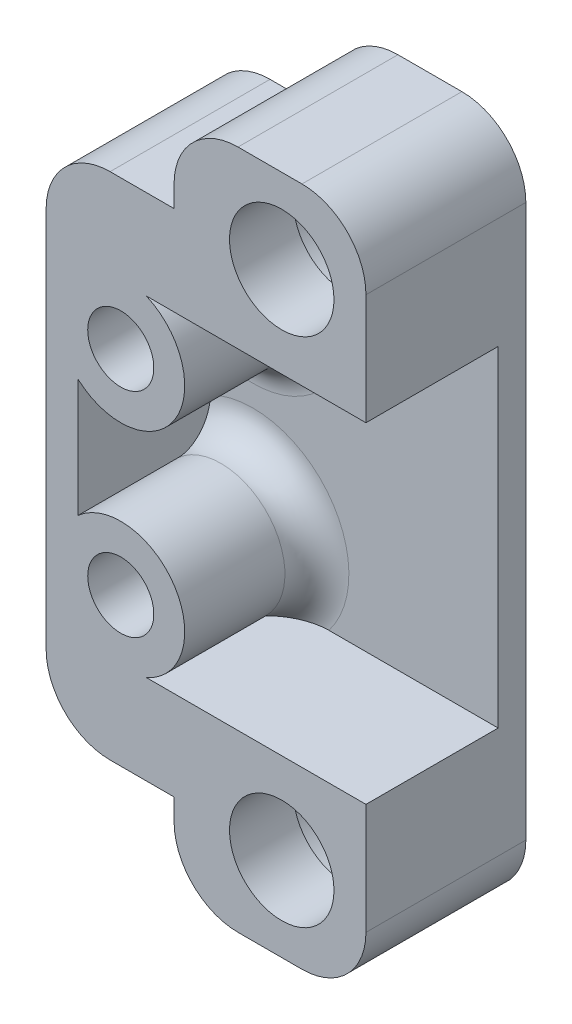
SolidWorks part; units mm, degrees
ref_plane "Front Plane" through (0, 0, 0) normal (0, 0, 1) x (1, 0, 0)
ref_plane "Top Plane" through (0, 0, 0) normal (0, 1, 0) x (1, 0, 0)
ref_plane "Right Plane" through (0, 0, 0) normal (1, 0, 0) x (0, 0, -1)
sketch "Sketch1" plane through (0, 0, 0) normal (0, 0, 1) x (1, 0, 0)
  line L0 (-10.2404, 15.95) -> (-10.2404, -15.95)
  line L1 (-6.2904, -12) -> (6.2904, -12)
  line L2 (-6.2904, -12) -> (-6.2904, 12)
  line L3 (-6.2904, 12) -> (6.2904, 12)
  line L4 (6.2904, -12) -> (6.2904, 12)
  line L5 (-6.2904, -12) -> (6.2904, 12) construction
  line L6 (-6.2904, 12) -> (6.2904, -12) construction
  line L7 (-8.7404, 14.45) -> (8.7404, 14.45)
  line L8 (-8.7404, 14.45) -> (-8.7404, -14.45)
  line L9 (-8.7404, -14.45) -> (8.7404, -14.45)
  line L10 (8.7404, 14.45) -> (8.7404, -14.45)
  line L11 (-8.7404, 14.45) -> (8.7404, -14.45) construction
  line L12 (-8.7404, -14.45) -> (8.7404, 14.45) construction
  line L13 (-10.2404, -15.95) -> (10.2404, -15.95)
  line L14 (10.2404, 15.95) -> (10.2404, -15.95)
  line L15 (-10.2404, 15.95) -> (10.2404, 15.95)
  circle A0 centre (6.2904, 12) radius 2.45
  circle A1 centre (6.2904, -12) radius 2.45
  point P0 (0, 0)
  point P8 (0, 0)
  dimension "D2" = 4.9
  dimension "D3" = 4.9
  dimension "D1" = 24
  dimension "D5" = 31.9
  dimension "D4" = 1.5
extrude "Boss-Extrude1" add sketch "Sketch1" along normal blind 7.5 contours L15 L0 L13 L14 L7 L10 L9 L8 | A0 L10 L7 | A1 L1 L2 L3 A0 L7 L8 L9 | A1 L10 A0 L4 | A1 L4 A0 L3 L2 L1 | A1 L9 L10
sketch "Sketch2" plane through (0, 0, 7.5) normal (0, 0, 1) x (1, 0, 0)
  line L0 (10.2404, 15.95) -> (8.7404, 15.95)
  line L1 (-10.2404, 15.95) -> (10.2404, 15.95) construction
  line L2 (8.7404, 15.95) -> (8.7404, -15.95)
  line L3 (-10.2404, -15.95) -> (10.2404, -15.95) construction
  line L4 (8.7404, 0) -> (-10.2404, 0)
  line L5 (-10.2404, 15.95) -> (-10.2404, -15.95) construction
  line L7 (-10.2404, -9.35) -> (8.7404, -9.35)
  line L8 (-10.2404, -9.35) -> (-10.2404, 9.35)
  line L9 (-10.2404, 9.35) -> (8.7404, 9.35)
  line L10 (8.7404, -9.35) -> (8.7404, 9.35)
  line L11 (-10.2404, -9.35) -> (8.7404, 9.35) construction
  line L12 (-10.2404, 9.35) -> (8.7404, -9.35) construction
  point P12 (-0.75, 0)
  line M11 (-10.2404, 15.95) -> (-10.2404, -15.95)
  dimension "D1" = 1.5
  dimension "D2" = 18.7
extrude "Cut-Extrude1" cut sketch "Sketch2" against normal blind 6.2 contours L9 L4 L2 M11 | L7 L2 L4 M11
sketch "Sketch3" plane through (0, 0, 1.3) normal (0, 0, 1) x (1, 0, 0)
  line L0 (10.2404, 0) -> (-1.2596, 0)
  line L1 (10.2404, 15.95) -> (10.2404, -15.95) construction
  line L2 (-1.2596, -5) -> (-1.2596, 5)
  circle A0 centre (-1.2596, 5) radius 1.55
  circle A1 centre (-1.2596, -5) radius 1.55
  circle A2 centre (-1.2596, 5) radius 3
  circle A3 centre (-1.2596, -5) radius 3
  point P7 (-1.2596, 0)
  dimension "D3" = 3.1
  dimension "D4" = 3.1
  dimension "D5" = 6
  dimension "D6" = 6
  dimension "D1" = 10
  dimension "D2" = 11.5
sketch "Sketch5" plane through (0, 0, 7.5) normal (0, 0, 1) x (1, 0, 0)
  line L0 (10.2404, 15.95) -> (-4.7596, 15.95)
  line L1 (-10.2404, 15.95) -> (10.2404, 15.95) construction
  line L3 (-4.7596, 15.95) -> (-10.2404, 15.95)
  line L4 (-4.7596, 15.95) -> (-4.7596, -15.95)
  line L5 (-4.7596, -15.95) -> (-10.2404, -15.95)
  line L6 (-10.2404, 15.95) -> (-10.2404, -15.95)
  line M6 (-10.2404, 15.95) -> (-10.2404, 9.35)
  line M7 (-10.2404, 9.35) -> (8.7404, 9.35)
  line M13 (10.2404, 15.95) -> (-10.2404, 15.95)
  dimension "D1" = 15
extrude "Cut-Extrude2" cut sketch "Sketch5" against normal up to surface (7.5 mm away) contours L4 M13 M6 M7
extrude "Boss-Extrude4" add sketch "Sketch3" along normal up to surface (6.2 mm away) up to face at (8.7404, 12, 7.5)
sketch "Sketch6" plane through (0, 0, 7.5) normal (0, 0, 1) x (1, 0, 0)
  line L0 (8.7404, 0) -> (10.2404, 0)
  line L1 (8.7404, 9.35) -> (8.7404, -9.35) construction
  line L2 (10.2404, 15.95) -> (10.2404, -15.95) construction
  line L8 (8.7404, -7.75) -> (10.2404, -7.75)
  line L9 (8.7404, -7.75) -> (8.7404, 7.75)
  line L10 (8.7404, 7.75) -> (10.2404, 7.75)
  line L11 (10.2404, -7.75) -> (10.2404, 7.75)
  line L12 (8.7404, -7.75) -> (10.2404, 7.75) construction
  line L13 (8.7404, 7.75) -> (10.2404, -7.75) construction
  point P6 (9.4904, 0)
  point P7 (9.4904, 0)
  dimension "D1" = 15.5
extrude "Cut-Extrude3" cut sketch "Sketch6" against normal up to surface (6.2 mm away)
sketch "Sketch7" plane through (0, 0, 1.3) normal (0, 0, 1) x (1, 0, 0)
  line L0 (-4.7596, -9.35) -> (8.7404, -9.35) construction
  line L1 (-4.7596, 9.35) -> (-3.2596, 9.35)
  line L2 (-4.7596, 9.35) -> (-4.7596, -9.35)
  line L3 (-4.7596, -9.35) -> (-3.2596, -9.35)
  line L4 (-3.2596, 9.35) -> (-3.2596, -9.35)
  dimension "D1" = 1.5
extrude "Boss-Extrude5" add sketch "Sketch7" along normal up to surface (6.2 mm away) contours L2 L1 L4 L3 up to face at (8.7404, 12, 7.5)
fillet "Fillet1" radius 3 2 edges at (10.2404, -15.95, 3.75) (10.2404, 15.95, 3.75)
sketch "Sketch8" plane through (0, 0, 7.5) normal (0, 0, 1) x (1, 0, 0)
  line L1 (-4.7596, 15.95) -> (1.2404, 15.95)
  line L2 (-4.7596, 15.95) -> (-4.7596, 11.95)
  line L3 (-4.7596, 11.95) -> (1.2404, 11.95)
  line L4 (1.2404, 15.95) -> (1.2404, 11.95)
  line L5 (-4.7596, -15.95) -> (1.2404, -15.95)
  line L6 (-4.7596, -15.95) -> (-4.7596, -11.95)
  line L7 (-4.7596, -11.95) -> (1.2404, -11.95)
  line L8 (1.2404, -15.95) -> (1.2404, -11.95)
  dimension "D1" = 4
  dimension "D2" = 4
  dimension "D3" = 6
  dimension "D4" = 6
extrude "Cut-Extrude4" cut sketch "Sketch8" against normal up to surface (7.5 mm away) contours L2 L1 L4 L3 | L6 L5 L8 L7 up to face at (8.7404, -12, 0)
fillet "Fillet2" radius 3 4 edges at (-4.7596, 11.95, 3.75) (1.2404, 15.95, 3.75) (1.2404, -15.95, 3.75) (-4.7596, -11.95, 3.75)
sketch "Sketch11" plane through (0, 0, 1.3) normal (0, 0, 1) x (1, 0, 0)
  line L0 (-3.2596, 7.2361) -> (-3.2596, 7.75)
  line L1 (8.7404, 7.75) -> (-0.0606, 7.75)
  line L2 (8.7404, 7.75) -> (8.7404, 9.35)
  line L3 (8.7404, 9.35) -> (-3.2596, 9.35)
  line L4 (-3.2596, 7.75) -> (-3.2596, 9.35)
  line L5 (0, 0) -> (4.7163, 0)
  line L6 (-3.2596, -7.75) -> (-3.2596, -9.35)
  line L7 (8.7404, -9.35) -> (-3.2596, -9.35)
  line L8 (8.7404, -7.75) -> (8.7404, -9.35)
  line L9 (8.7404, -7.75) -> (-0.0606, -7.75)
  line L10 (-3.2596, -7.2361) -> (-3.2596, -7.75)
  arc A0 (-0.0606, 7.75) -> (-3.2596, 7.2361) centre (-1.2596, 5) ccw
  arc A1 (-0.0606, -7.75) -> (-3.2596, -7.2361) centre (-1.2596, -5) cw
extrude "Boss-Extrude6" add sketch "Sketch11" along normal up to surface and the other way up to surface up to face at (8.7404, -12, 7.5) other way up to face at (8.7404, 12, 0)
sketch "Sketch10" plane through (0, 0, 0) normal (0, 0, -1) x (-1, 0, 0)
  circle A0 centre (-6.2904, 12) radius 3.25
  circle A1 centre (-6.2904, -12) radius 3.25
  dimension "D1" = 6.5
  dimension "D2" = 6.5
extrude "Cut-Extrude6" cut sketch "Sketch10" against normal blind 4.5
fillet "Fillet3" radius 1.5 2 edges at (1.2654, 3.38, 1.3) (1.2654, -3.38, 1.3)
